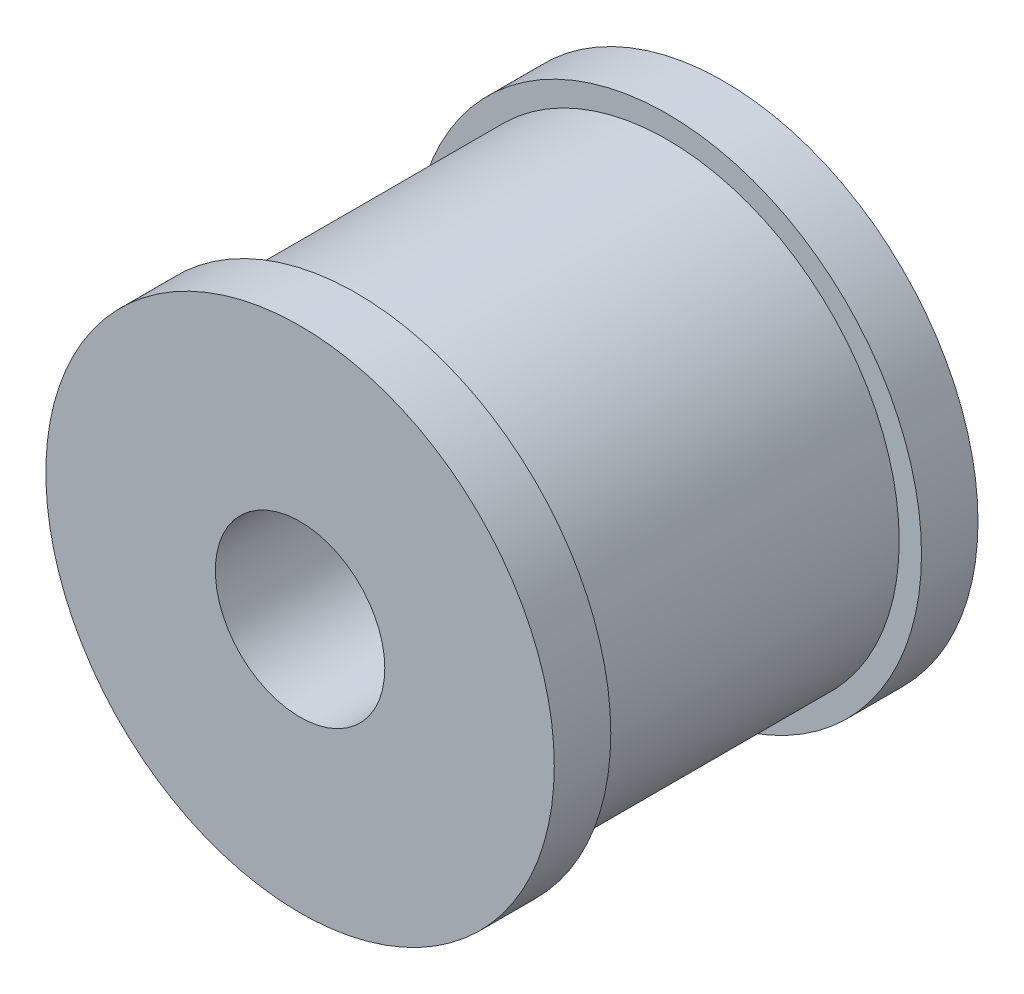
SolidWorks part; units mm, degrees
ref_plane "前视基准面" through (0, 0, 0) normal (0, 0, 1) x (1, 0, 0)
ref_plane "上视基准面" through (0, 0, 0) normal (0, 1, 0) x (1, 0, 0)
ref_plane "右视基准面" through (0, 0, 0) normal (1, 0, 0) x (0, 0, -1)
sketch "草图1" plane through (0, 0, 0) normal (0, 0, 1) x (1, 0, 0)
  circle A0 centre (0, 0) radius 3
  circle A1 centre (0, 0) radius 9
  dimension "D1" = 18
  dimension "D2" = 6
extrude "凸台-拉伸1" add sketch "草图1" along normal blind 15 contours A1
ref_plane "基准面1" through (0, 0, 7.5) normal (0, 0, 1) x (1, 0, 0)
sketch "草图3" plane through (0, 0, 7.5) normal (0, 0, 1) x (1, 0, 0)
  circle A0 centre (0, 0) radius 8.21
  dimension "D1" = 16.42
extrude "切除-拉伸-薄壁1" cut sketch "草图3" against normal blind 5.5 and the other way blind 5.5 thin
